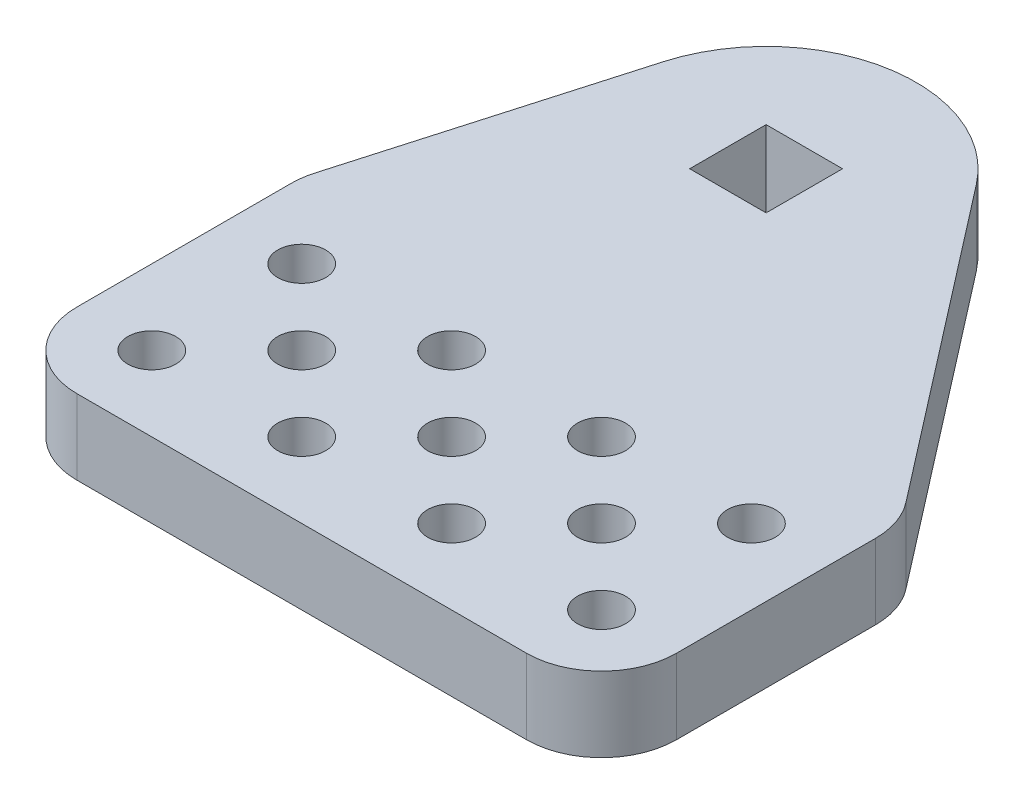
SolidWorks part; units mm, degrees
ref_plane "Front Plane" through (0, 0, 0) normal (0, 0, 1) x (1, 0, 0)
ref_plane "Top Plane" through (0, 0, 0) normal (0, 1, 0) x (1, 0, 0)
ref_plane "Right Plane" through (0, 0, 0) normal (1, 0, 0) x (0, 0, -1)
sketch "Sketch1" plane through (0, 0, 0) normal (0, 1, 0) x (1, 0, 0)
  line L0 (0, 25.4) -> (6.8445, 49.2049)
  line L1 (0, 0) -> (50.8, 0)
  line L2 (0, 0) -> (0, 25.4)
  line L4 (50.8, 0) -> (50.8, 25.4)
  line L5 (29.0963, 53.4648) -> (50.8, 25.4)
  line L6 (38.1, 12.7) -> (19.05, 45.6956) construction
  line L7 (15.8115, 42.4571) -> (22.2885, 42.4571)
  line L8 (15.8115, 42.4571) -> (15.8115, 48.9341)
  line L9 (15.8115, 48.9341) -> (22.2885, 48.9341)
  line L10 (22.2885, 42.4571) -> (22.2885, 48.9341)
  line L11 (15.8115, 42.4571) -> (22.2885, 48.9341) construction
  line L12 (15.8115, 48.9341) -> (22.2885, 42.4571) construction
  arc A1 (6.8445, 49.2049) -> (29.0963, 53.4648) centre (19.05, 45.6956) cw
  circle A2 centre (6.35, 6.35) radius 2.032
  circle A3 centre (19.05, 6.35) radius 2.032
  circle A4 centre (31.75, 6.35) radius 2.032
  circle A5 centre (44.45, 6.35) radius 2.032
  circle A6 centre (19.05, 19.05) radius 2.032
  circle A7 centre (31.75, 19.05) radius 2.032
  circle A8 centre (44.45, 19.05) radius 2.032
  circle A9 centre (6.35, 19.05) radius 2.032
  circle A10 centre (12.7, 12.7) radius 2.032
  circle A11 centre (25.4, 12.7) radius 2.032
  circle A12 centre (38.1, 12.7) radius 2.032
  dimension "D3" = 6.477
  dimension "D6" = 12.7
  dimension "D7" = 6.35
  dimension "D8" = 4.064
  dimension "D12" = 12.7
  dimension "D1" = 25.4
  dimension "D2" = 50.8
  dimension "D4" = 38.1
  dimension "D5" = 19.05
  dimension "D9" = 6.35
  dimension "D13" = 12.7
  dimension "D15" = 25.4
  dimension "D10" = 4
  dimension "D11" = 2
  dimension "D14" = 3
extrude "Boss-Extrude1" add sketch "Sketch1" along normal blind 6.35
fillet "Fillet1" radius 6.35 4 edges at (50.8, 3.175, -25.4) (50.8, 3.175, 0) (0, 3.175, 0) (0, 3.175, -25.4)
